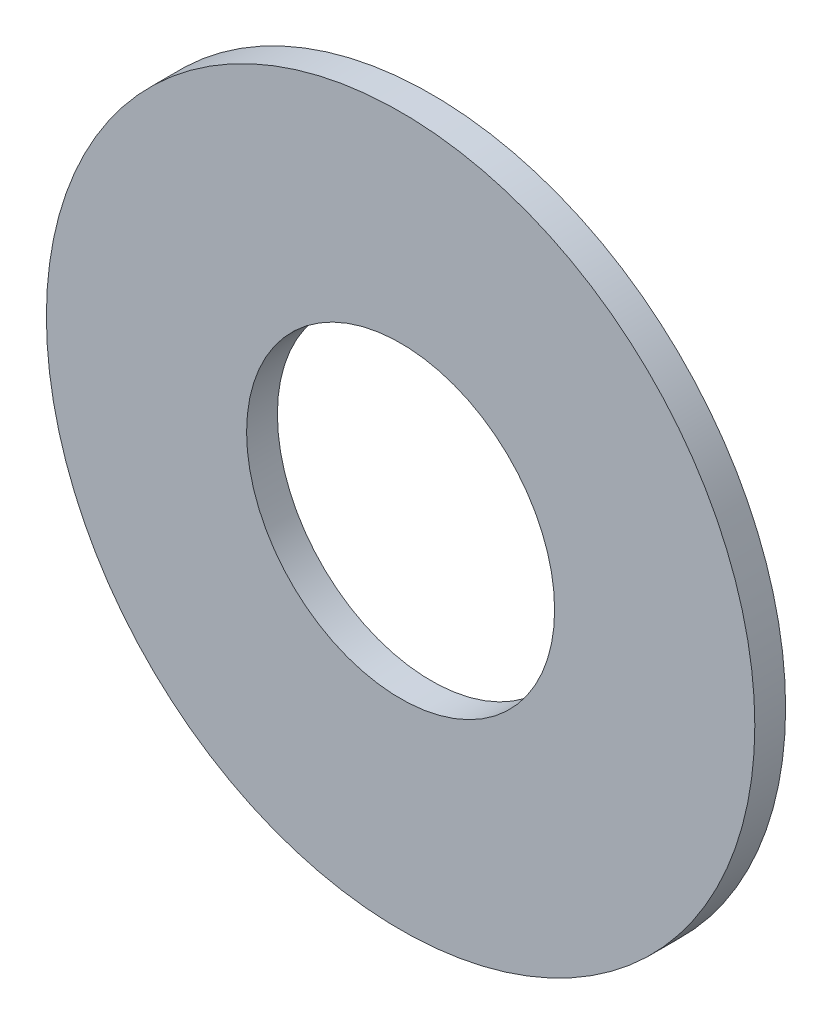
SolidWorks part; units mm, degrees
ref_plane "Front Plane" through (0, 0, 0) normal (0, 0, 1) x (1, 0, 0)
ref_plane "Top Plane" through (0, 0, 0) normal (0, 1, 0) x (1, 0, 0)
ref_plane "Right Plane" through (0, 0, 0) normal (1, 0, 0) x (0, 0, -1)
sketch "Sketch1" plane through (0, 0, 0) normal (0, 0, 1) x (1, 0, 0)
  circle A0 centre (0, 0) radius 29.21
  circle A1 centre (0, 0) radius 12.7
  dimension "D1" = 58.42
  dimension "D2" = 25.4
extrude "Boss-Extrude1" add sketch "Sketch1" along normal blind 2.54
